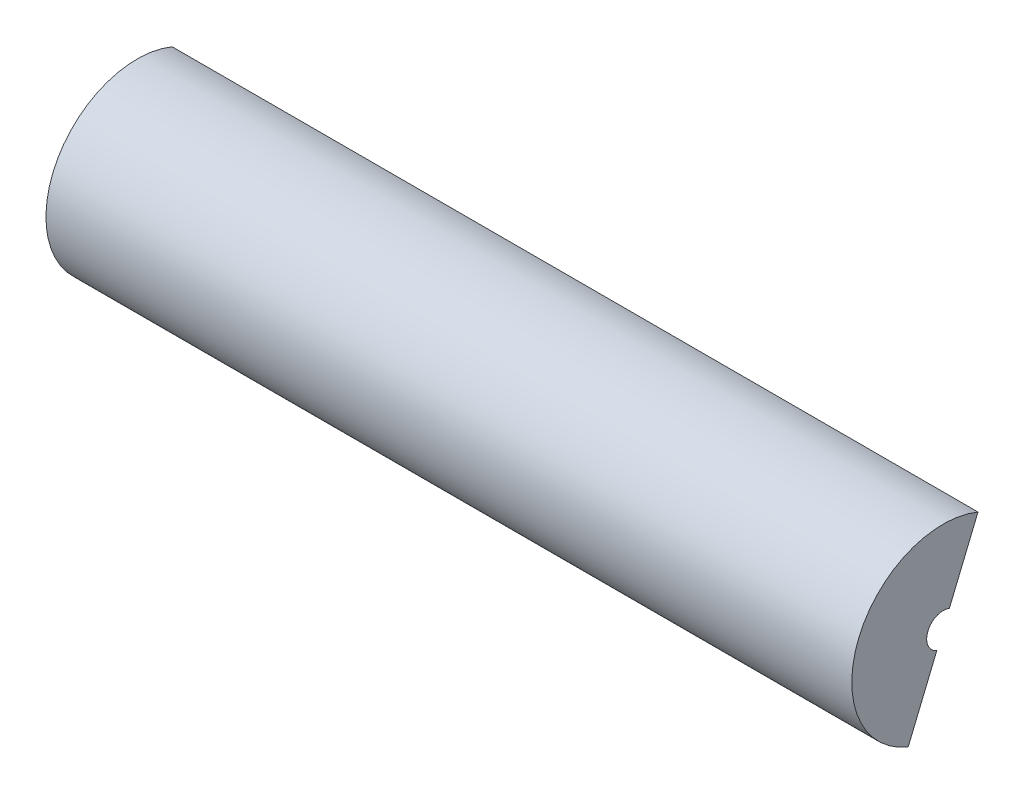
SolidWorks part; units mm, degrees
ref_plane "Front Plane" through (0, 0, 0) normal (0, 0, 1) x (1, 0, 0)
ref_plane "Top Plane" through (0, 0, 0) normal (0, 1, 0) x (1, 0, 0)
ref_plane "Right Plane" through (0, 0, 0) normal (1, 0, 0) x (0, 0, -1)
sketch "Sketch1" plane through (0, 0, 0) normal (0, 0, 1) x (1, 0, 0)
  line L0 (0, 12.7) -> (196.85, 12.7)
  line L1 (196.85, 12.7) -> (196.85, 26.162)
  line L2 (196.85, 26.162) -> (241.3, 26.162)
  line L3 (241.3, 26.162) -> (241.3, 0)
  line L6 (0, 12.7) -> (0, 31)
  line L8 (259.36, 10.7696) -> (259.36, 0)
  line L9 (259.36, 0) -> (241.3, 0)
  line L10 (0, 0) -> (298.2335, 0) construction
  line L11 (259.36, 10.7696) -> (273.6661, 5.5626)
  line L12 (273.6661, 5.5626) -> (273.6661, 31)
  line L14 (273.6661, 31) -> (0, 31)
  point P12 (259.36, 5.3848)
  dimension "D1" = 26.162
  dimension "D2" = 12.7
  dimension "D3" = 62
  dimension "D4" = 44.45
  dimension "D5" = 196.85
  dimension "D6" = 18.06
  dimension "D7" = 10.7696
  dimension "D8" = 5.5626
  dimension "D9" = 14.3061
revolve "Revolve1" add sketch "Sketch1" angle 360 about L10
sketch "Sketch3" plane through (241.3, 0, 0) normal (-1, 0, 0) x (0, 0, 1)
  line L0 (-2.4786, 5.984) -> (2.4786, -5.984) construction
  line L1 (0, 6.477) -> (0, -6.477) construction
  circle A1 centre (0, 0) radius 6.477 construction
  circle A2 centre (0, 6.477) radius 0.8065
  circle A3 centre (4.5799, 4.5799) radius 0.8065
  circle A4 centre (6.477, 0) radius 0.8065
  circle A5 centre (4.5799, -4.5799) radius 0.8065
  circle A6 centre (0, -6.477) radius 0.8065
  circle A7 centre (-4.5799, -4.5799) radius 0.8065
  circle A8 centre (-6.477, 0) radius 0.8065
  circle A9 centre (-4.5799, 4.5799) radius 0.8065
  point P21 (0, 0)
  point P22 (-1.4336, 6.477)
  point P23 (-2.4616, 5.991)
  dimension "D1" = 12.954
  dimension "D2" = 1.6129
  dimension "D4" = 22.5
  dimension "D3" = 8
extrude "Cut-Extrude1" cut sketch "Sketch3" against normal up to next
ref_plane "Plane2" through (0, 0, 0) normal (0, 0.3827, 0.9239) x (0, -0.9239, 0.3827)
sketch "Sketch4" plane through (0, 0, 0) normal (0, 0.3827, 0.9239) x (0, -0.9239, 0.3827)
  line L1 (-31, 273.6661) -> (31, 273.6661)
  line L2 (-31, 273.6661) -> (-31, 0)
  line L3 (-31, 0) -> (31, 0)
  line L4 (31, 273.6661) -> (31, 0)
extrude "Cut-Extrude2" cut sketch "Sketch4" against normal through all
